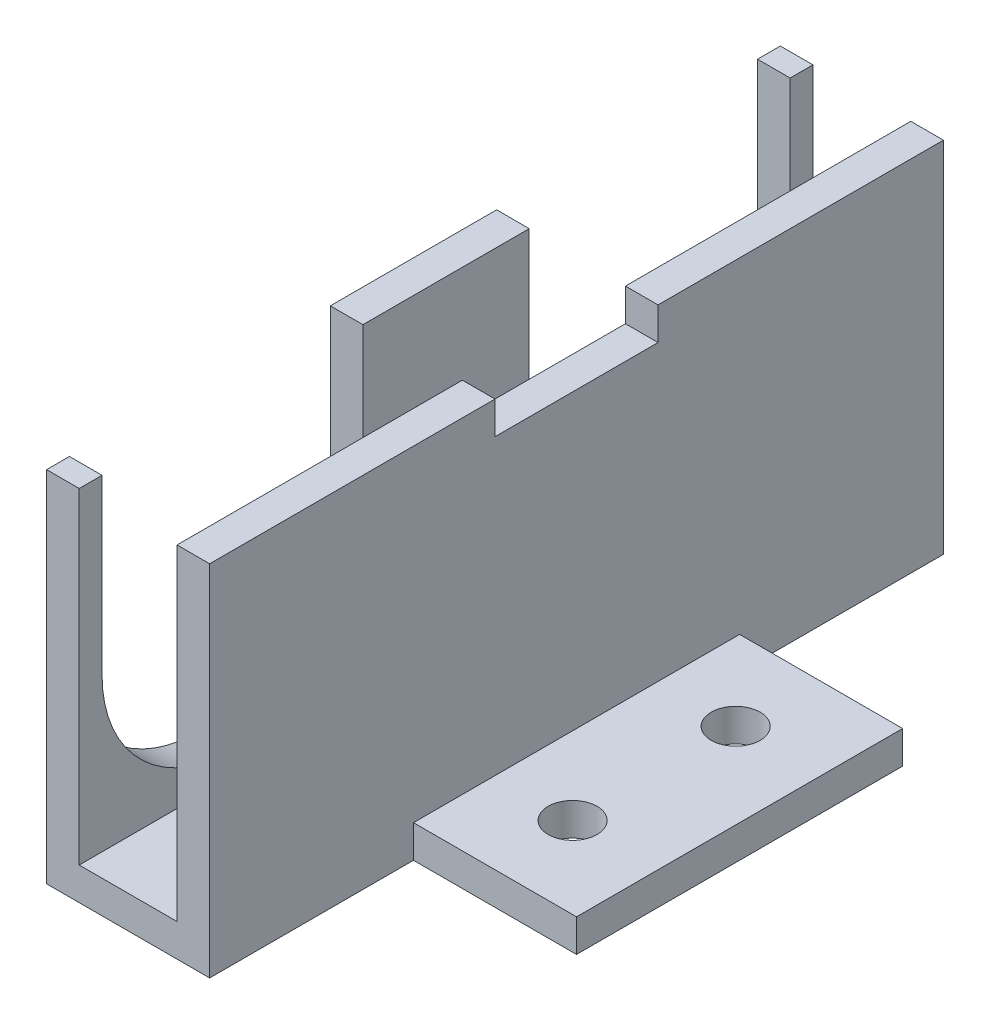
SolidWorks part; units mm, degrees
ref_plane "Front Plane" through (0, 0, 0) normal (0, 0, 1) x (1, 0, 0)
ref_plane "Top Plane" through (0, 0, 0) normal (0, 1, 0) x (1, 0, 0)
ref_plane "Right Plane" through (0, 0, 0) normal (1, 0, 0) x (0, 0, -1)
sketch "Sketch1" plane through (0, 0, 0) normal (0, 0, 1) x (1, 0, 0)
  line L0 (0, 0) -> (6, 0)
  line L1 (6, 0) -> (6, 20)
  line L2 (6, 20) -> (8, 20)
  line L3 (8, 20) -> (8, -2)
  line L4 (8, -2) -> (-2, -2)
  line L5 (-2, -2) -> (-2, 20)
  line L6 (-2, 20) -> (0, 20)
  line L7 (0, 20) -> (0, 0)
  dimension "D1" = 20
  dimension "D2" = 2
  dimension "D3" = 2
  dimension "D4" = 2
  dimension "D5" = 6
extrude "Boss-Extrude1" add sketch "Sketch1" along normal blind 45
sketch "Sketch3" plane through (-2, 0, 0) normal (-1, 0, 0) x (0, 0, 1)
  line L0 (0, 20) -> (0, -2) construction
  line L1 (45, 20) -> (45, -2) construction
  line L2 (45, 20) -> (0, 20) construction
  line L3 (1.4, 9.4075) -> (17.4, 9.4075)
  line L4 (1.4, 9.4075) -> (1.4, 20)
  line L5 (1.4, 20) -> (17.4, 20)
  line L6 (17.4, 9.4075) -> (17.4, 20)
  line L8 (27.6, 9.4075) -> (43.6, 9.4075)
  line L9 (27.6, 9.4075) -> (27.6, 20)
  line L10 (27.6, 20) -> (43.6, 20)
  line L11 (43.6, 9.4075) -> (43.6, 20)
  circle A0 centre (9.4, 9.4075) radius 8
  circle A1 centre (35.6, 9.4075) radius 8
  line M4 (45, 20) -> (0, 20)
  dimension "D1" = 9.4
  dimension "D2" = 9.4
  dimension "D3" = 26.2
extrude "Cut-Extrude1" cut sketch "Sketch3" against normal blind 2 contours L8 A1 | A0 L6 L4 M4 | L3 A0 | A1 L11 L9 M4 | L8 A1 | L3 A0
sketch "Sketch4" plane through (8, 0, 0) normal (1, 0, 0) x (0, 0, -1)
  line L0 (-45, 20) -> (0, 20) construction
  line L1 (-27.5, 20) -> (-17.5, 20)
  line L2 (-27.5, 20) -> (-27.5, 18)
  line L3 (-27.5, 18) -> (-17.5, 18)
  line L4 (-17.5, 20) -> (-17.5, 18)
  line L5 (-45, -2) -> (-45, 20) construction
  line L6 (0, -2) -> (0, 20) construction
  dimension "D1" = 2
  dimension "D2" = 10
  dimension "D3" = 17.5
  dimension "D4" = 17.5
extrude "Cut-Extrude2" cut sketch "Sketch4" against normal blind 2
sketch "Sketch5" plane through (8, 0, 0) normal (1, 0, 0) x (0, 0, -1)
  line L0 (-45, -2) -> (0, -2) construction
  line L1 (-32.5, 0) -> (-12.5, 0)
  line L2 (-32.5, 0) -> (-32.5, -2)
  line L3 (-32.5, -2) -> (-12.5, -2)
  line L4 (-12.5, 0) -> (-12.5, -2)
  line L5 (-45, -2) -> (-45, 20) construction
  dimension "D1" = 2
  dimension "D2" = 20
  dimension "D3" = 12.5
extrude "Boss-Extrude2" add sketch "Sketch5" along normal blind 10
sketch "Sketch6" plane through (0, 0, 0) normal (0, 1, 0) x (1, 0, 0)
  line L0 (18, -12.5) -> (8, -12.5) construction
  line L1 (18, -32.5) -> (8, -32.5) construction
  circle A0 centre (12.7602, -27.5) radius 1.5
  circle A1 centre (12.7602, -17.5) radius 1.5
  dimension "D1" = 5
  dimension "D2" = 5
extrude "Cut-Extrude3" cut sketch "Sketch6" against normal blind 2
